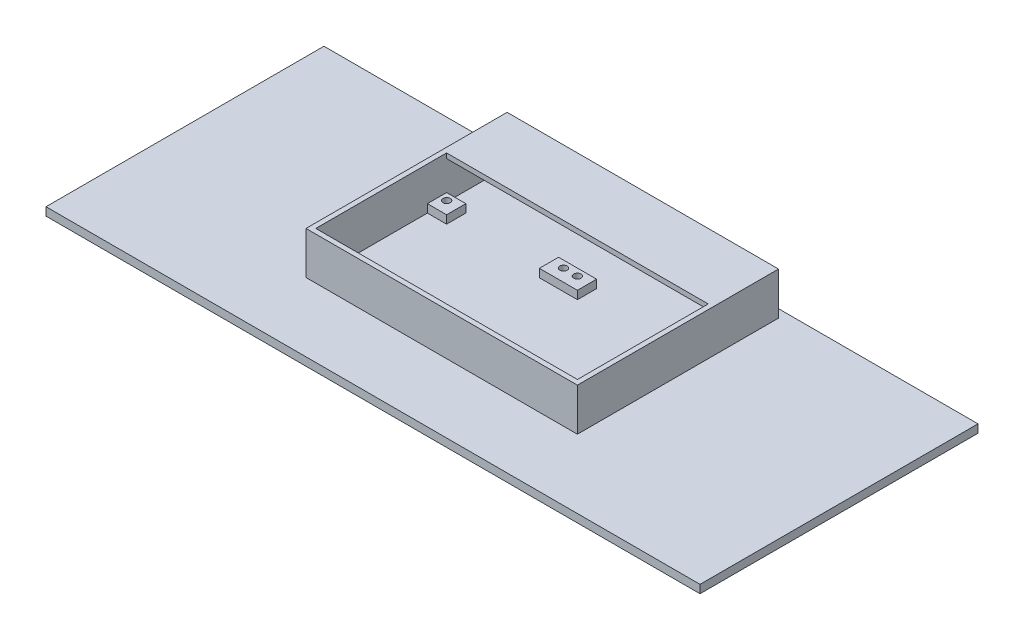
SolidWorks part; units mm, degrees
ref_plane "Ebene vorne" through (0, 0, 0) normal (0, 0, 1) x (1, 0, 0)
ref_plane "Ebene oben" through (0, 0, 0) normal (0, 1, 0) x (1, 0, 0)
ref_plane "Ebene rechts" through (0, 0, 0) normal (1, 0, 0) x (0, 0, -1)
sketch "Skizze1" plane through (0, 0, 0) normal (0, 1, 0) x (1, 0, 0)
  line L1 (-200, -85) -> (200, -85)
  line L2 (-200, -85) -> (-200, 85)
  line L3 (-200, 85) -> (200, 85)
  line L4 (200, -85) -> (200, 85)
  line L5 (-200, -85) -> (200, 85) construction
  line L6 (-200, 85) -> (200, -85) construction
  point P0 (0, 0)
  dimension "D1" = 170
  dimension "D2" = 400
extrude "Aufsatz-Linear austragen1" add sketch "Skizze1" along normal blind 5
sketch "Skizze3" plane through (0, 5, 0) normal (0, 1, 0) x (1, 0, 0)
  line L6 (-80, -40) -> (0, -40) construction
  line L7 (-80, -40) -> (-80, 40) construction
  line L8 (-80, 40) -> (0, 40) construction
  line L9 (0, -40) -> (0, 40) construction
  line L10 (-80, -40) -> (0, 40) construction
  line L11 (-80, 40) -> (0, -40) construction
  line L12 (0, -40) -> (80, -40) construction
  line L13 (0, -40) -> (0, 40) construction
  line L14 (0, 40) -> (80, 40) construction
  line L15 (80, -40) -> (80, 40) construction
  line L16 (0, -40) -> (80, 40) construction
  line L17 (0, 40) -> (80, -40) construction
  line L37 (68.25, 40) -> (80, 40)
  line L42 (-80, 40) -> (-68.25, 40)
  line L43 (-80, 40) -> (-80, 28.25)
  line L44 (-80, 28.25) -> (-68.25, 28.25)
  line L45 (-68.25, 40) -> (-68.25, 28.25)
  line L46 (68.25, 40) -> (68.25, 28.25)
  line L47 (68.25, 28.25) -> (80, 28.25)
  line L48 (80, 40) -> (80, 28.25)
  line L50 (-80, -40) -> (-68.25, -40)
  line L51 (-80, -40) -> (-80, -28.25)
  line L52 (-80, -28.25) -> (-68.25, -28.25)
  line L53 (-68.25, -40) -> (-68.25, -28.25)
  line L54 (80, -40) -> (68.5, -40)
  line L55 (80, -40) -> (80, -28.5)
  line L56 (80, -28.5) -> (68.5, -28.5)
  line L57 (68.5, -40) -> (68.5, -28.5)
  line L58 (-11.75, -40) -> (11.75, -40)
  line L59 (-11.75, -40) -> (-11.75, -28.25)
  line L60 (-11.75, -28.25) -> (11.75, -28.25)
  line L61 (11.75, -40) -> (11.75, -28.25)
  line L62 (-11.5, 40) -> (11.75, 40)
  line L63 (-11.5, 40) -> (-11.5, 28.25)
  line L64 (-11.5, 28.25) -> (11.75, 28.25)
  line L65 (11.75, 40) -> (11.75, 28.25)
  circle A0 centre (-75.75, 35.75) radius 2.25
  circle A1 centre (-4.25, 35.75) radius 2.25
  circle A2 centre (-4.25, -35.75) radius 2.25
  circle A3 centre (-75.75, -35.75) radius 2.25
  circle A9 centre (4.25, -35.75) radius 2.25
  circle A10 centre (76, -36) radius 2.25
  circle A11 centre (4.25, 35.75) radius 2.25
  circle A12 centre (75.75, 35.75) radius 2.25
  point P0 (-40, 0)
  point P6 (40, 0)
  dimension "D4" = 4.5
  dimension "D7" = 71.5
  dimension "D1" = 71.5
  dimension "D2" = 80
  dimension "D3" = 80
  dimension "D6" = 71.5
  dimension "D12" = 11.75
  dimension "D13" = 4.25
  dimension "D14" = 7.5
  dimension "D15" = 11.75
  dimension "D16" = 7.5
  dimension "D17" = 7.5
  dimension "D18" = 7.5
  dimension "D19" = 7.5
  dimension "D20" = 7.5
  dimension "D21" = 7.5
  dimension "D22" = 7.5
  dimension "D23" = 7.5
  dimension "D24" = 7.5
  dimension "D25" = 4.25
extrude "Aufsatz-Linear austragen6" add sketch "Skizze3" along normal blind 5
sketch "Skizze4" plane through (0, 5, 0) normal (0, 1, 0) x (1, 0, 0)
  line L0 (200, 85) -> (-200, 85) construction
  line L1 (80, -40) -> (83, -40)
  line L2 (80, -40) -> (80, 80)
  line L3 (80, 80) -> (83, 80)
  line L4 (83, -40) -> (83, 80)
  line L6 (-80, -40) -> (-83, -40)
  line L7 (-80, -40) -> (-80, 80)
  line L8 (-80, 80) -> (-83, 80)
  line L9 (-83, -40) -> (-83, 80)
  line L10 (-83, -40) -> (83, -40)
  line L11 (-83, -40) -> (-83, -43)
  line L12 (-83, -43) -> (83, -43)
  line L13 (83, -40) -> (83, -43)
  line M13 (80, 40) -> (80, 28.25)
  line M15 (-80, 28.25) -> (-80, 40)
  line M22 (11.75, -40) -> (-11.75, -40)
  line M23 (80, -28.5) -> (80, -40)
  line M24 (80, -40) -> (68.5, -40)
  line M27 (-80, -40) -> (-80, -28.25)
  line M30 (-68.25, -40) -> (-80, -40)
  dimension "D1" = 3
  dimension "D2" = 5
  dimension "D3" = 3
  dimension "D4" = 3
extrude "Aufsatz-Linear austragen7" add sketch "Skizze4" along normal blind 26 contours L9 L6 L7 L8 M27 M15 | L13 L1 L10 L6 L11 L12 M24 M22 M30 | L1 L4 L3 L2 M13 M23
sketch "Skizze6" plane through (0, 31, 0) normal (0, 1, 0) x (1, 0, 0)
  line L1 (-80, 40) -> (80, 40)
  line L2 (-80, 40) -> (-80, 80)
  line L3 (-80, 80) -> (80, 80)
  line L4 (80, 40) -> (80, 80)
extrude "Aufsatz-Linear austragen8" add sketch "Skizze6" against normal blind 3
